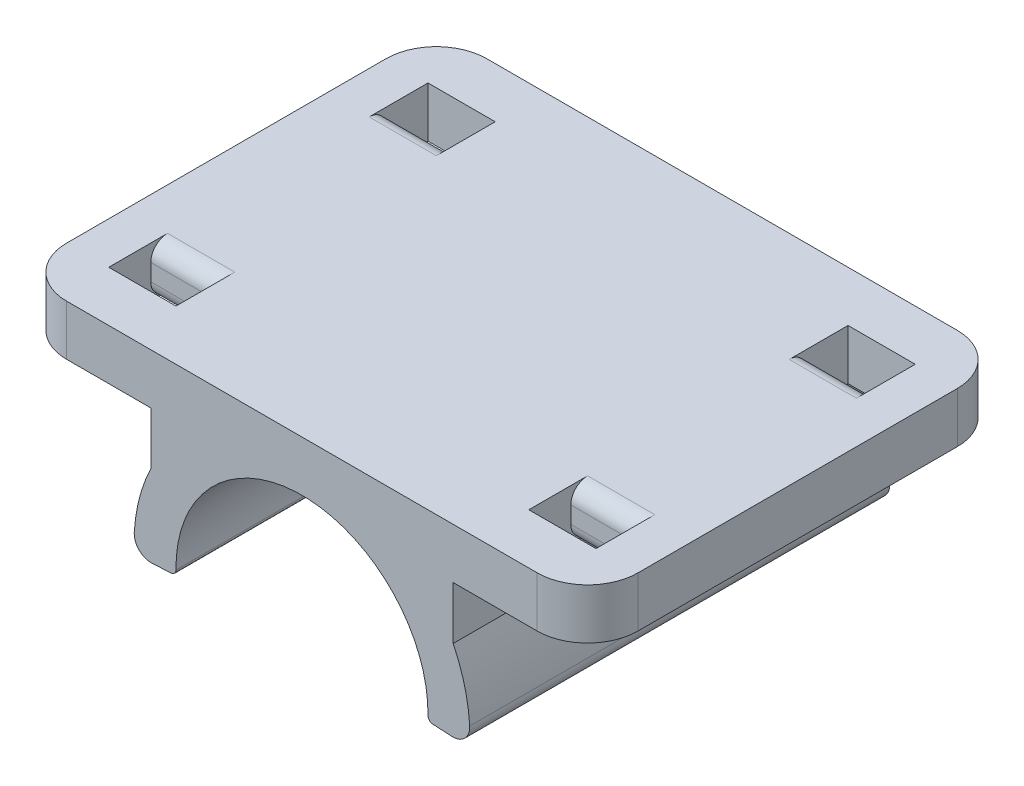
SolidWorks part; units mm, degrees
ref_plane "Plano frontal" through (0, 0, 0) normal (0, 0, 1) x (1, 0, 0)
ref_plane "Plano superior" through (0, 0, 0) normal (0, 1, 0) x (1, 0, 0)
ref_plane "Plano direito" through (0, 0, 0) normal (1, 0, 0) x (0, 0, -1)
sketch "Esboço1" plane through (0, 0, 0) normal (0, 0, 1) x (1, 0, 0)
  line L0 (-17, 10.5) -> (17, 10.5)
  line L1 (-7.7835, -0.4079) -> (-9.9863, -0.5234)
  line L2 (0, 0) -> (-10, 0) construction
  line L3 (0, 0) -> (0, 10.5) construction
  line L4 (7.7835, -0.4079) -> (9.9863, -0.5234)
  line L5 (-17, 10.5) -> (-17, 7.5)
  line L6 (-17, 7.5) -> (-9, 7.5)
  line L7 (-9, 7.5) -> (-9, 4.3589)
  line L8 (9, 7.5) -> (9, 4.3589)
  line L9 (17, 7.5) -> (9, 7.5)
  line L10 (17, 10.5) -> (17, 7.5)
  arc A0 (7.4993, -0.1042) -> (-7.4993, -0.1042) centre (0, 0) ccw
  arc A1 (9.9863, -0.5234) -> (9, 4.3589) centre (0, 0) ccw
  arc A2 (7.7835, -0.4079) -> (7.4993, -0.1042) centre (7.7992, -0.1083) cw
  arc A3 (-7.7835, -0.4079) -> (-7.4993, -0.1042) centre (-7.7992, -0.1083) ccw
  arc A4 (-9, 4.3589) -> (-9.9863, -0.5234) centre (0, 0) ccw
  point P6 (0, 10.5)
  point P13 (7.4897, -0.3925)
  point P16 (-7.4897, -0.3925)
  dimension "D1" = 15
  dimension "D3" = 20
  dimension "D5" = 0.3
  dimension "D2" = 10.5
  dimension "D4" = 3
  dimension "D6" = 3
  dimension "D7" = 9
  dimension "D8" = 8
extrude "Ressalto-extrusão1" add sketch "Esboço1" along normal blind 25
fillet "Filete1" radius 1 2 edges at (9.9863, -0.5234, 12.5) (-9.9863, -0.5234, 12.5)
sketch "Esboço3" plane through (0, 10.5, 0) normal (0, 1, 0) x (1, 0, 0)
  line L0 (-12.5, -12.5) -> (12.5, -12.5) construction
  line L1 (17, -25) -> (17, 0) construction
  line L2 (-12.5, -4.25) -> (-12.5, -20.75) construction
  line L3 (0, 0) -> (0, -25) construction
  line L4 (17, -25) -> (-17, -25) construction
  line L5 (17, 0) -> (-17, 0) construction
  line L6 (-14.5, -3) -> (-10.5, -3)
  line L7 (-14.5, -3) -> (-14.5, -5.5)
  line L8 (-14.5, -5.5) -> (-10.5, -5.5)
  line L9 (-10.5, -3) -> (-10.5, -5.5)
  line L10 (-14.5, -3) -> (-10.5, -5.5) construction
  line L11 (-14.5, -5.5) -> (-10.5, -3) construction
  line L13 (-14.5, -19.5) -> (-10.5, -22) construction
  line L14 (-14.5, -22) -> (-10.5, -19.5) construction
  line L15 (-10.5, -22) -> (-10.5, -19.5)
  line L16 (-14.5, -19.5) -> (-10.5, -19.5)
  line L17 (-14.5, -22) -> (-14.5, -19.5)
  line L18 (-14.5, -22) -> (-10.5, -22)
  line L19 (12.5, -4.25) -> (12.5, -20.75) construction
  line L20 (14.5, -22) -> (10.5, -19.5) construction
  line L21 (14.5, -19.5) -> (10.5, -22) construction
  line L22 (14.5, -5.5) -> (10.5, -3) construction
  line L23 (14.5, -3) -> (10.5, -5.5) construction
  line L24 (14.5, -22) -> (10.5, -22)
  line L25 (14.5, -22) -> (14.5, -19.5)
  line L26 (14.5, -19.5) -> (10.5, -19.5)
  line L27 (10.5, -22) -> (10.5, -19.5)
  line L28 (10.5, -3) -> (10.5, -5.5)
  line L29 (14.5, -5.5) -> (10.5, -5.5)
  line L30 (14.5, -3) -> (14.5, -5.5)
  line L31 (14.5, -3) -> (10.5, -3)
  point P3 (0, -12.5)
  point P6 (17, -12.5)
  point P10 (-12.5, -12.5)
  point P15 (0, -12.5)
  dimension "D1" = 25
  dimension "D2" = 4
  dimension "D3" = 2.5
  dimension "D4" = 3
extrude "Corte-extrusão1" cut sketch "Esboço3" against normal up to next
fillet "Filete2" radius 1 8 edges at (-12.5, 7.5, 5.5) (12.5, 7.5, 5.5) (12.5, 7.5, 19.5) (12.5, 10.5, 19.5) (12.5, 10.5, 5.5) (-12.5, 7.5, 19.5) (-12.5, 10.5, 19.5) (-12.5, 10.5, 5.5)
fillet "Filete3" radius 3 4 edges at (-17, 9, 0) (17, 9, 0) (17, 9, 25) (-17, 9, 25)
